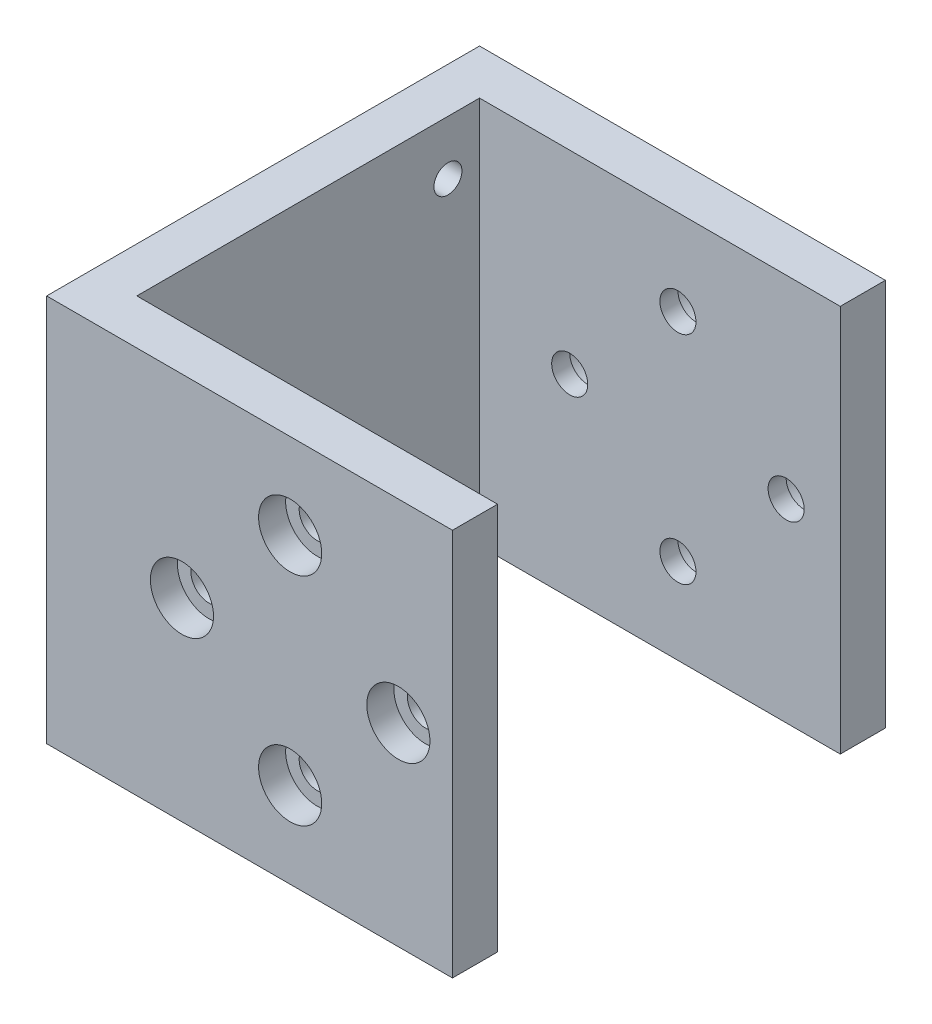
SolidWorks part; units mm, degrees
ref_plane "Front Plane" through (0, 0, 0) normal (0, 0, 1) x (1, 0, 0)
ref_plane "Top Plane" through (0, 0, 0) normal (0, 1, 0) x (1, 0, 0)
ref_plane "Right Plane" through (0, 0, 0) normal (1, 0, 0) x (0, 0, -1)
sketch "Sketch1" plane through (0, 0, 0) normal (1, 0, 0) x (0, 0, -1)
  line L1 (24, -21.5) -> (-24, -21.5)
  line L2 (24, -21.5) -> (24, 21.5)
  line L3 (24, 21.5) -> (-24, 21.5)
  line L4 (-24, -21.5) -> (-24, 21.5)
  line L5 (24, -21.5) -> (-24, 21.5) construction
  line L6 (24, 21.5) -> (-24, -21.5) construction
  point P0 (0, 0)
  dimension "D1" = 43
  dimension "D2" = 48
extrude "Boss-Extrude1" add sketch "Sketch1" along normal blind 5
sketch "Sketch2" plane through (5, 0, 0) normal (1, 0, 0) x (0, 0, -1)
  line L1 (-15.5, -15.5) -> (15.5, -15.5) construction
  line L2 (-15.5, -15.5) -> (-15.5, 15.5) construction
  line L3 (-15.5, 15.5) -> (15.5, 15.5) construction
  line L4 (15.5, -15.5) -> (15.5, 15.5) construction
  line L5 (-15.5, -15.5) -> (15.5, 15.5) construction
  line L6 (-15.5, 15.5) -> (15.5, -15.5) construction
  circle A0 centre (-15.5, 15.5) radius 1.55
  circle A1 centre (15.5, 15.5) radius 1.55
  circle A2 centre (15.5, -15.5) radius 1.55
  circle A3 centre (-15.5, -15.5) radius 1.55
  point P0 (0, 0)
  point P16 (0, 0)
  dimension "D3" = 3.1
  dimension "D1" = 31
  dimension "D2" = 31
  dimension "D4" = 4
extrude "Cut-Extrude1" cut sketch "Sketch2" against normal up to next
sketch "Sketch4" plane through (5, 0, 0) normal (1, 0, 0) x (0, 0, -1)
  line L0 (-24, -21.5) -> (24, -21.5) construction
  line L1 (-24, 21.5) -> (-19, 21.5)
  line L2 (-24, 21.5) -> (-24, -21.5)
  line L3 (-24, -21.5) -> (-19, -21.5)
  line L4 (-19, 21.5) -> (-19, -21.5)
  line L5 (-21.5, -21.5) -> (-21.5, 21.5) construction
  line L6 (-24, 0) -> (-19, 0) construction
  point P80 (-21.5, 0)
  dimension "D1" = 5
extrude "Boss-Extrude2" add sketch "Sketch4" along normal blind 40
sketch "Sketch6" plane through (0, 0, 24) normal (0, 0, 1) x (1, 0, 0)
  line L0 (27, 0) -> (0, 0) construction
  circle A0 centre (27, 0) radius 12 construction
  circle A1 centre (27, 12) radius 2
  circle A2 centre (39, 0) radius 2
  circle A3 centre (27, -12) radius 2
  circle A4 centre (15, 0) radius 2
  point P6 (27, 0)
  dimension "D1" = 24
  dimension "D3" = 4
  dimension "D4" = 4
  dimension "D2" = 27
extrude "Cut-Extrude2" cut sketch "Sketch6" against normal up to next
sketch "Sketch7" plane through (0, 0, 24) normal (0, 0, 1) x (1, 0, 0)
  line L0 (27, 12) -> (27, -12) construction
  line L1 (15, 0) -> (39, 0) construction
  circle A0 centre (27, 12) radius 3.5
  circle A1 centre (39, 0) radius 3.5
  circle A2 centre (27, -12) radius 3.5
  circle A3 centre (15, 0) radius 3.5
  dimension "D1" = 7
  dimension "D2" = 7
  dimension "D3" = 7
  dimension "D4" = 7
extrude "Cut-Extrude3" cut sketch "Sketch7" against normal blind 3
mirror "Mirror2" about plane through (0, 0, 0) normal (0, 0, 1) of "Cut-Extrude2", "Cut-Extrude3", "Boss-Extrude2"
